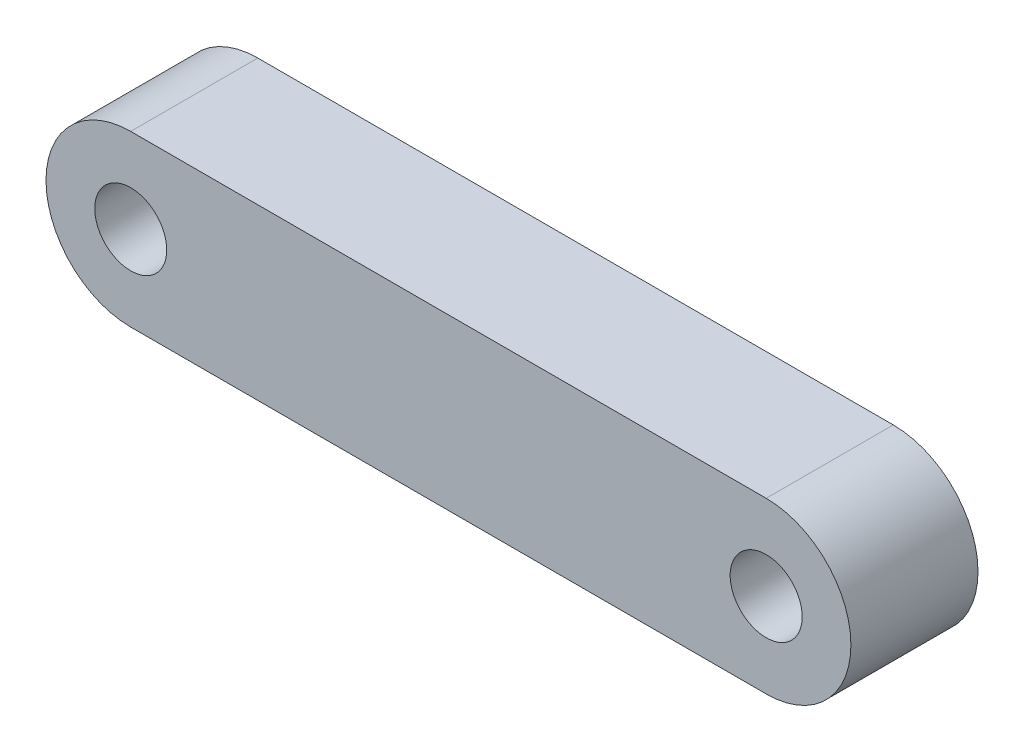
SolidWorks part; units mm, degrees
ref_plane "前视基准面" through (0, 0, 0) normal (0, 0, 1) x (1, 0, 0)
ref_plane "上视基准面" through (0, 0, 0) normal (0, 1, 0) x (1, 0, 0)
ref_plane "右视基准面" through (0, 0, 0) normal (1, 0, 0) x (0, 0, -1)
sketch "草图1" plane through (0, 0, 0) normal (0, 0, 1) x (1, 0, 0)
  line L0 (0, 0) -> (30, 0) construction
  line L1 (0, 4) -> (30, 4)
  line L2 (0, -4) -> (30, -4)
  arc A0 (0, 4) -> (0, -4) centre (0, 0) ccw
  arc A1 (30, -4) -> (30, 4) centre (30, 0) ccw
  point P3 (15, 0)
  dimension "D1" = 4
  dimension "D2" = 30
extrude "凸台-拉伸1" add sketch "草图1" along normal blind 6
sketch "草图2" plane through (0, 0, 6) normal (0, 0, 1) x (1, 0, 0)
  circle A0 centre (0, 0) radius 1.7
  circle A1 centre (30, 0) radius 1.7
  dimension "D1" = 3.4
extrude "切除-拉伸1" cut sketch "草图2" against normal blind 10
